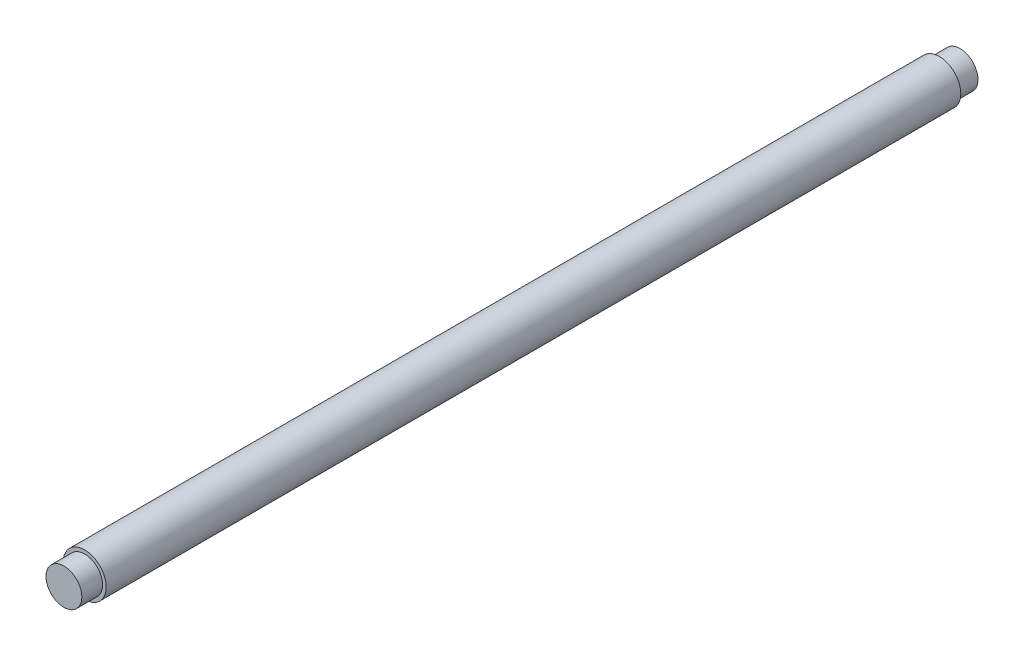
SolidWorks part; units mm, degrees
ref_plane "正面" through (0, 0, 0) normal (0, 0, 1) x (1, 0, 0)
ref_plane "平面" through (0, 0, 0) normal (0, 1, 0) x (1, 0, 0)
ref_plane "右側面" through (0, 0, 0) normal (1, 0, 0) x (0, 0, -1)
sketch "ｽｹｯﾁ1" plane through (0, 0, 0) normal (0, 0, 1) x (1, 0, 0)
  circle A0 centre (0, 0) radius 6
  dimension "D1" = 12
extrude "ﾎﾞｽ - 押し出し1" add sketch "ｽｹｯﾁ1" along normal blind 250
sketch "ｽｹｯﾁ2" plane through (0, 0, 250) normal (0, 0, 1) x (1, 0, 0)
  circle A0 centre (0, 0) radius 6
  circle A1 centre (0, 0) radius 5
  circle A2 centre (0, 0) radius 6 construction
  dimension "D1" = 10
extrude "ｶｯﾄ - 押し出し1" cut sketch "ｽｹｯﾁ2" against normal blind 5.8
ref_plane "平面1" through (0, 0, 125) normal (0, 0, 1) x (1, 0, 0)
mirror "ﾐﾗｰ1" about plane through (0, 0, 125) normal (0, 0, 1) of "ｶｯﾄ - 押し出し1"
